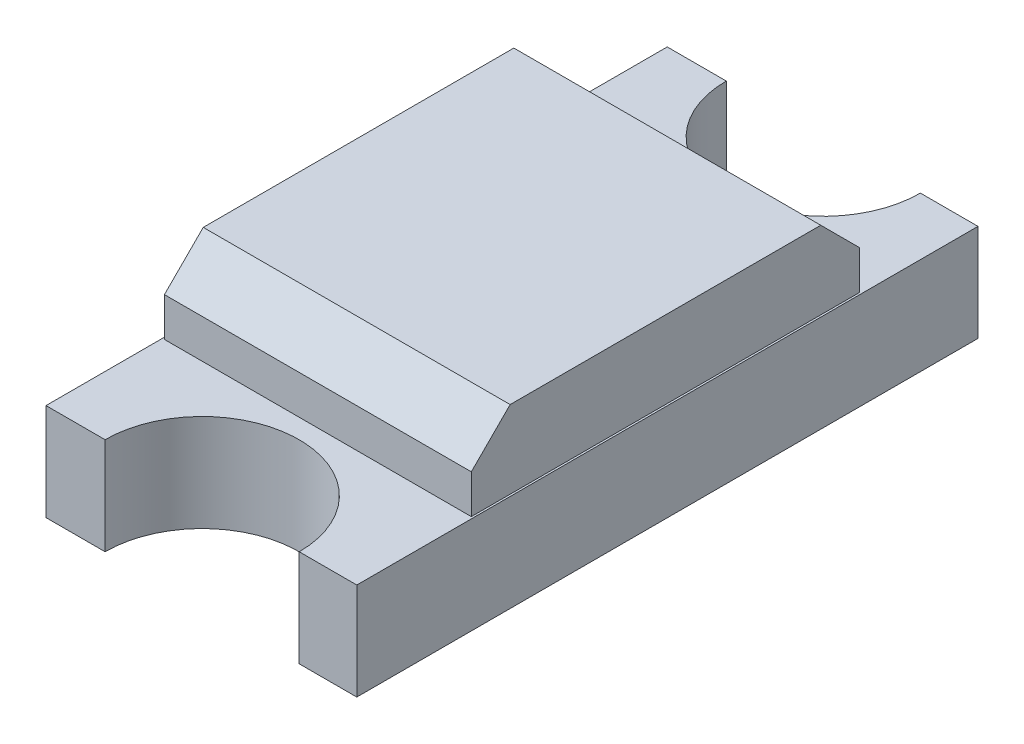
SolidWorks part; units mm, degrees
ref_plane "Front" through (0, 0, 0) normal (0, 0, 1) x (1, 0, 0)
ref_plane "Top" through (0, 0, 0) normal (0, 1, 0) x (1, 0, 0)
ref_plane "Right" through (0, 0, 0) normal (1, 0, 0) x (0, 0, -1)
sketch "Sketch1" plane through (0, 0, 0) normal (0, 1, 0) x (1, 0, 0)
  line L0 (-0.5, 0) -> (-0.8043, 0)
  line L1 (-0.8043, 0) -> (-0.8043, -3.2)
  line L2 (-0.8043, -3.2) -> (-0.5, -3.2)
  line L3 (0.5, 0) -> (0.7966, 0)
  line L4 (0.7966, 0) -> (0.7966, -3.2)
  line L5 (0.7966, -3.2) -> (0.5, -3.2)
  arc A0 (0.5, 0) -> (-0.5, 0) centre (0, 0) cw
  arc A1 (0.5, -3.2) -> (-0.5, -3.2) centre (0, -3.2) ccw
  dimension "D1" = 0.5
  dimension "D2" = 0.5
  dimension "D3" = 3.2
  dimension "D4" = 1.601
  dimension "D5" = 0.3043
  dimension "D6" = 0.3043
  dimension "D7" = 0.2966
extrude "Boss-Extrude1" add sketch "Sketch1" along normal blind 0.5
sketch "Sketch2" plane through (0, 0.5, 0) normal (0, 1, 0) x (1, 0, 0)
  line L0 (-0.8043, 0) -> (-0.8043, -3.2) construction
  line L1 (-0.7943, -2.6) -> (0.7866, -2.6)
  line L2 (-0.7943, -2.6) -> (-0.7943, -0.6)
  line L3 (-0.7943, -0.6) -> (0.7866, -0.6)
  line L4 (0.7866, -2.6) -> (0.7866, -0.6)
  line L5 (0.7966, -3.2) -> (0.7966, 0) construction
  line L6 (0.7966, -3.2) -> (0.7966, 0) construction
  point P8 (0.7966, -1.6)
  dimension "D1" = 0.01
  dimension "D2" = 0.01
  dimension "D3" = 2
  dimension "D4" = 1
extrude "Boss-Extrude3" add sketch "Sketch2" along normal blind 0.4
chamfer "Chamfer2" distance 0.2 angle 45 2 edges at (-0.0039, 0.9, 2.6) (-0.0039, 0.9, 0.6)
